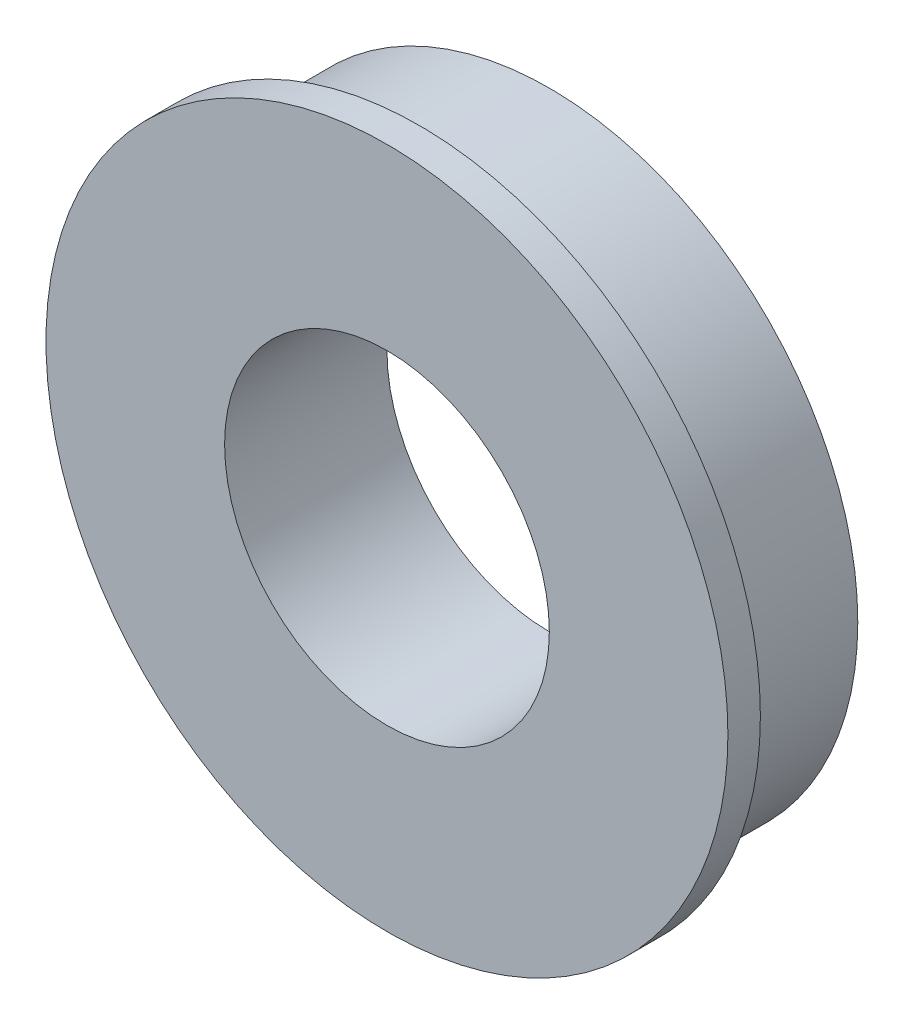
SolidWorks part; units mm, degrees
material "黄铜"
ref_plane "前视基准面" through (0, 0, 0) normal (0, 0, 1) x (1, 0, 0)
ref_plane "上视基准面" through (0, 0, 0) normal (0, 1, 0) x (1, 0, 0)
ref_plane "右视基准面" through (0, 0, 0) normal (1, 0, 0) x (0, 0, -1)
sketch "草图1" plane through (0, 0, 0) normal (0, 0, 1) x (1, 0, 0)
  circle A0 centre (0, 0) radius 5
  circle A1 centre (0, 0) radius 9.5
extrude "凸台-拉伸1" add sketch "草图1" along normal blind 4
sketch "草图2" plane through (0, 0, 4) normal (0, 0, 1) x (1, 0, 0)
  circle A0 centre (0, 0) radius 5
  circle A1 centre (0, 0) radius 10.5
extrude "凸台-拉伸2" add sketch "草图2" along normal blind 1
